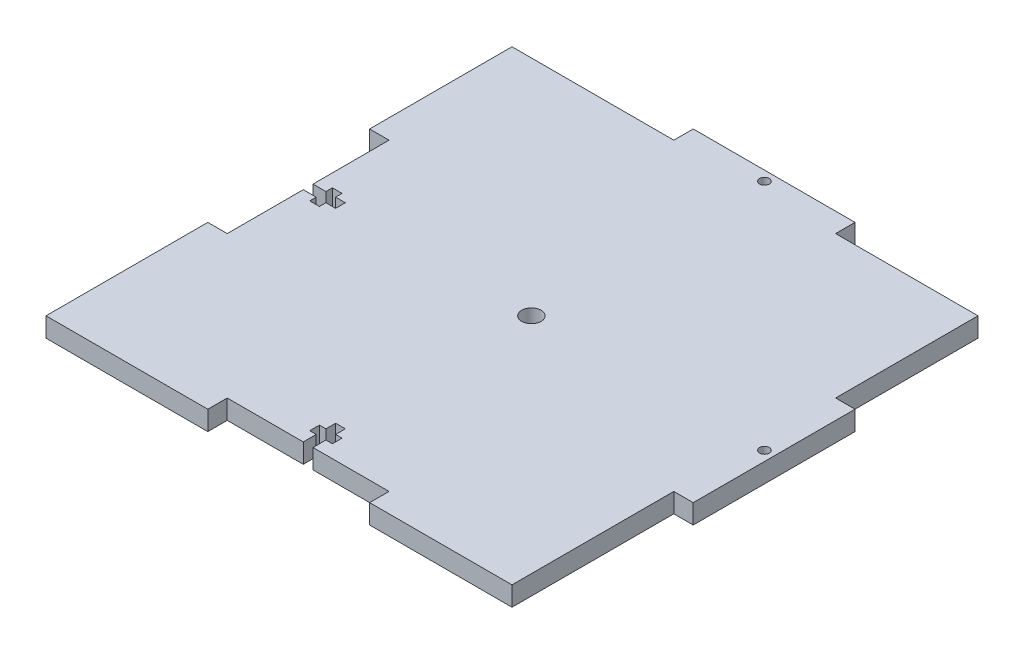
SolidWorks part; units mm, degrees
material "Acrylic (Medium-high impact)"
ref_plane "Front Plane" through (0, 0, 0) normal (0, 0, 1) x (1, 0, 0)
ref_plane "Top Plane" through (0, 0, 0) normal (0, 1, 0) x (1, 0, 0)
ref_plane "Right Plane" through (0, 0, 0) normal (1, 0, 0) x (0, 0, -1)
sketch "Sketch1" plane through (0, 0, 0) normal (0, 1, 0) x (1, 0, 0)
  line L0 (-72, 28) -> (-66, 28)
  line L1 (-72, -72) -> (72, -72)
  line L2 (-72, -72) -> (-72, 72)
  line L3 (-72, 72) -> (72, 72)
  line L4 (72, -72) -> (72, 72)
  line L5 (-72, -72) -> (72, 72) construction
  line L6 (-72, 72) -> (72, -72) construction
  line L7 (-66, 28) -> (-66, -22)
  line L8 (28, -72) -> (28, -66)
  line L9 (-22, 72) -> (-22, 78)
  line L10 (-22, 78) -> (28, 78)
  line L11 (28, 72) -> (28, 78)
  line L12 (72, 28) -> (78, 28)
  line L13 (78, 28) -> (78, -22)
  line L14 (-22, -72) -> (-22, -66)
  line L15 (-22, -66) -> (28, -66)
  line L16 (3, 78) -> (3, -72) construction
  line L17 (-72, 3) -> (78, 3) construction
  line L18 (72, -22) -> (78, -22)
  line L19 (-72, -22) -> (-66, -22)
  line L20 (75, 28) -> (75, -22) construction
  line L21 (4.5, -66) -> (4.5, -62)
  line L22 (4.5, -62) -> (6.5, -62)
  line L23 (6.5, -62) -> (6.5, -59)
  line L24 (6.5, -59) -> (4.5, -59)
  line L25 (4.5, -59) -> (4.5, -56)
  line L26 (4.5, -56) -> (1.5, -56)
  line L27 (1.5, -66) -> (1.5, -62)
  line L28 (1.5, -62) -> (-0.5, -62)
  line L29 (-0.5, -59) -> (1.5, -59)
  line L30 (-0.5, -62) -> (-0.5, -59)
  line L31 (1.5, -59) -> (1.5, -56)
  line L32 (-59, 4.5) -> (-56, 4.5)
  line L33 (-62, 4.5) -> (-62, 6.5)
  line L34 (-59, 6.5) -> (-59, 4.5)
  line L35 (-62, 6.5) -> (-59, 6.5)
  line L36 (-66, 4.5) -> (-62, 4.5)
  line L37 (-66, 1.5) -> (-62, 1.5)
  line L38 (-62, 1.5) -> (-62, -0.5)
  line L39 (-62, -0.5) -> (-59, -0.5)
  line L40 (-59, -0.5) -> (-59, 1.5)
  line L41 (-59, 1.5) -> (-56, 1.5)
  line L42 (-56, 4.5) -> (-56, 1.5)
  circle A0 centre (75, 3) radius 1.5
  circle A1 centre (3, 75) radius 1.5
  circle A2 centre (3, 3) radius 3
  point P0 (0, 0)
  point P22 (3, 3)
  point P27 (3, 3)
  point P40 (3, -66)
  point P45 (-66, 3)
  point P49 (3, -56)
  dimension "D4" = 3
  dimension "D9" = 6
  dimension "D1" = 144
  dimension "D2" = 25
  dimension "D3" = 6
  dimension "D5" = 4
  dimension "D6" = 2
  dimension "D7" = 3
  dimension "D8" = 1.5
extrude "Boss-Extrude1" add sketch "Sketch1" along normal blind 6 contours L19 L2 L1 L14 L15 L8 L4 L3 L0 L7 | L3 L11 L10 L9 | L4 L18 L13 L12
